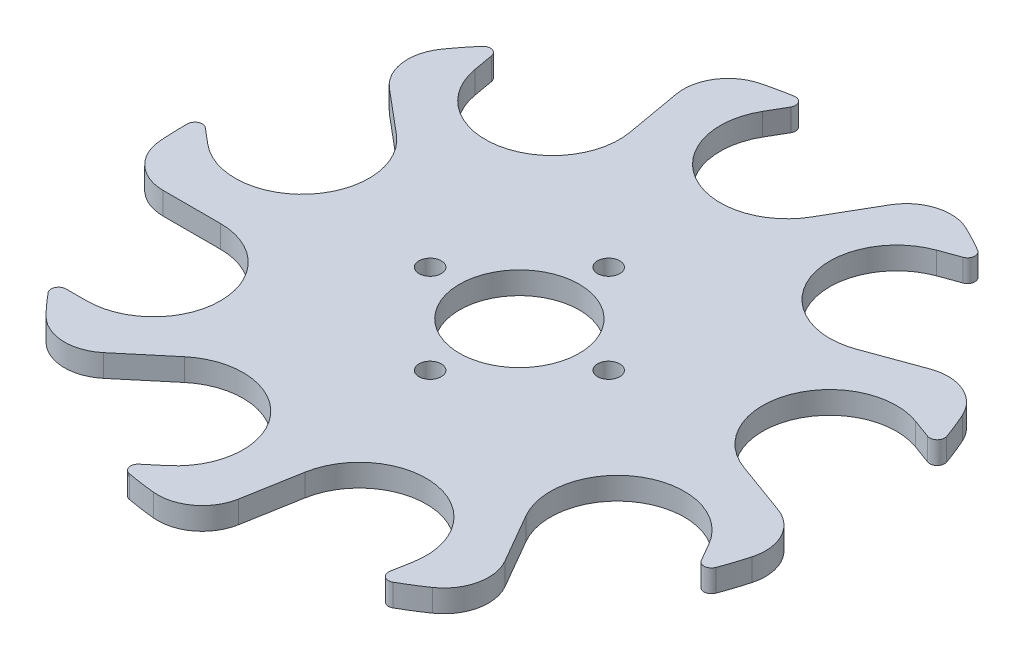
SolidWorks part; units mm, degrees
ref_plane "前视基准面" through (0, 0, 0) normal (0, 0, 1) x (1, 0, 0)
ref_plane "上视基准面" through (0, 0, 0) normal (0, 1, 0) x (1, 0, 0)
ref_plane "右视基准面" through (0, 0, 0) normal (1, 0, 0) x (0, 0, -1)
ref_plane "基准面4" through (0, 3, 0) normal (0, 1, 0) x (1, 0, 0)
sketch "草图1" plane through (0, 3, 0) normal (0, 1, 0) x (1, 0, 0)
  line L0 (-38.8844, -9) -> (-31.1769, -9)
  line L1 (-31.1769, -27) -> (-33.9411, -27)
  line L2 (-24.0021, -31.8888) -> (-18.0978, -26.9345)
  line L3 (-6.5276, -40.7233) -> (-8.6451, -42.5001)
  line L4 (2.1111, -39.8565) -> (3.4495, -32.2661)
  line L5 (21.176, -35.3918) -> (20.696, -38.114)
  line L6 (27.2365, -29.1749) -> (23.3827, -22.5)
  line L7 (38.9711, -13.5) -> (40.3532, -15.8939)
  line L8 (39.6176, -4.842) -> (32.3749, -2.2059)
  line L9 (38.5313, 14.7086) -> (41.1288, 13.7632)
  line L10 (33.4612, 21.7565) -> (26.2185, 19.1204)
  line L11 (20.0622, 36.0348) -> (22.6597, 36.9802)
  line L12 (11.648, 38.1749) -> (7.7942, 31.5)
  line L13 (-7.7942, 40.5) -> (-6.4121, 42.8939)
  line L14 (-15.6155, 36.7309) -> (-14.2771, 29.1404)
  line L15 (-32.0036, 26.0148) -> (-32.4836, 28.737)
  line L16 (-35.5723, 18.1) -> (-29.668, 13.1457)
  line L17 (-41.2382, -0.6431) -> (-43.3557, 1.1337)
  arc A0 (-31.1769, -9) -> (-31.1769, -27) centre (-31.1769, -18) cw
  arc A1 (-33.9411, -27) -> (-34.7125, -28.6364) centre (-33.9411, -28) ccw
  arc A2 (-34.7125, -28.6364) -> (-32.1448, -31.4914) centre (0, 0) ccw
  arc A3 (-32.1448, -31.4914) -> (-24.0021, -31.8888) centre (-27.8588, -27.2926) ccw
  arc A4 (-18.0978, -26.9345) -> (-6.5276, -40.7233) centre (-12.3127, -33.8289) cw
  arc A5 (-8.6451, -42.5001) -> (-8.1842, -44.2495) centre (-8.0024, -43.2662) ccw
  arc A6 (-8.1842, -44.2495) -> (-4.3821, -44.7861) centre (0, 0) ccw
  arc A7 (-4.3821, -44.7861) -> (2.1111, -39.8565) centre (-3.7978, -38.8146) ccw
  arc A8 (3.4495, -32.2661) -> (21.176, -35.3918) centre (12.3127, -33.8289) cw
  arc A9 (20.696, -38.114) -> (22.1735, -39.1578) centre (21.6808, -38.2876) ccw
  arc A10 (22.1735, -39.1578) -> (25.4311, -37.1249) centre (0, 0) ccw
  arc A11 (25.4311, -37.1249) -> (27.2365, -29.1749) centre (22.0403, -32.1749) ccw
  arc A12 (23.3827, -22.5) -> (38.9711, -13.5) centre (31.1769, -18) cw
  arc A13 (40.3532, -15.8939) -> (42.1561, -15.7437) centre (41.2193, -15.3939) ccw
  arc A14 (42.1561, -15.7437) -> (43.3448, -12.0925) centre (0, 0) ccw
  arc A15 (43.3448, -12.0925) -> (39.6176, -4.842) centre (37.5655, -10.4802) ccw
  arc A16 (32.3749, -2.2059) -> (38.5313, 14.7086) centre (35.4531, 6.2513) cw
  arc A17 (41.1288, 13.7632) -> (42.4133, 15.037) centre (41.4708, 14.7028) ccw
  arc A18 (42.4133, 15.037) -> (40.977, 18.5981) centre (0, 0) ccw
  arc A19 (40.977, 18.5981) -> (33.4612, 21.7565) centre (35.5134, 16.1183) ccw
  arc A20 (26.2185, 19.1204) -> (20.0622, 36.0348) centre (23.1404, 27.5776) cw
  arc A21 (22.6597, 36.9802) -> (22.8249, 38.7818) centre (22.3177, 37.9199) ccw
  arc A22 (22.8249, 38.7818) -> (19.4356, 40.5864) centre (0, 0) ccw
  arc A23 (19.4356, 40.5864) -> (11.648, 38.1749) centre (16.8441, 35.1749) ccw
  arc A24 (7.7942, 31.5) -> (-7.7942, 40.5) centre (0, 36) cw
  arc A25 (-6.4121, 42.8939) -> (-7.4436, 44.3801) centre (-7.2781, 43.3939) ccw
  arc A26 (-7.4436, 44.3801) -> (-11.2, 43.584) centre (0, 0) ccw
  arc A27 (-11.2, 43.584) -> (-15.6155, 36.7309) centre (-9.7066, 37.7728) ccw
  arc A28 (-14.2771, 29.1404) -> (-32.0036, 26.0148) centre (-23.1404, 27.5776) cw
  arc A29 (-32.4836, 28.737) -> (-34.2291, 29.2125) centre (-33.4684, 28.5633) ccw
  arc A30 (-34.2291, 29.2125) -> (-36.5949, 26.188) centre (0, 0) ccw
  arc A31 (-36.5949, 26.188) -> (-35.5723, 18.1) centre (-31.7156, 22.6963) ccw
  arc A32 (-29.668, 13.1457) -> (-41.2382, -0.6431) centre (-35.4531, 6.2513) cw
  arc A33 (-43.3557, 1.1337) -> (-44.9984, 0.376) centre (-43.9985, 0.3677) ccw
  arc A34 (-44.9984, 0.376) -> (-44.8667, -3.4615) centre (0, 0) ccw
  arc A35 (-44.8667, -3.4615) -> (-38.8844, -9) centre (-38.8844, -3) ccw
  circle A36 centre (0, 0) radius 8.05
  circle A37 centre (0, 0) radius 12 construction
  circle A38 centre (0, 12) radius 1.5
  circle A39 centre (12, 0) radius 1.5
  circle A40 centre (0, -12) radius 1.5
  circle A41 centre (0, 0) radius 45 construction
  circle A42 centre (-12, 0) radius 1.5
  point P96 (0, 0)
  dimension "D1" = 90
  dimension "D2" = 16.1
  dimension "D3" = 24
  dimension "D4" = 3
  dimension "D5" = 4
extrude "凸台-拉伸1" add sketch "草图1" against normal blind 3
